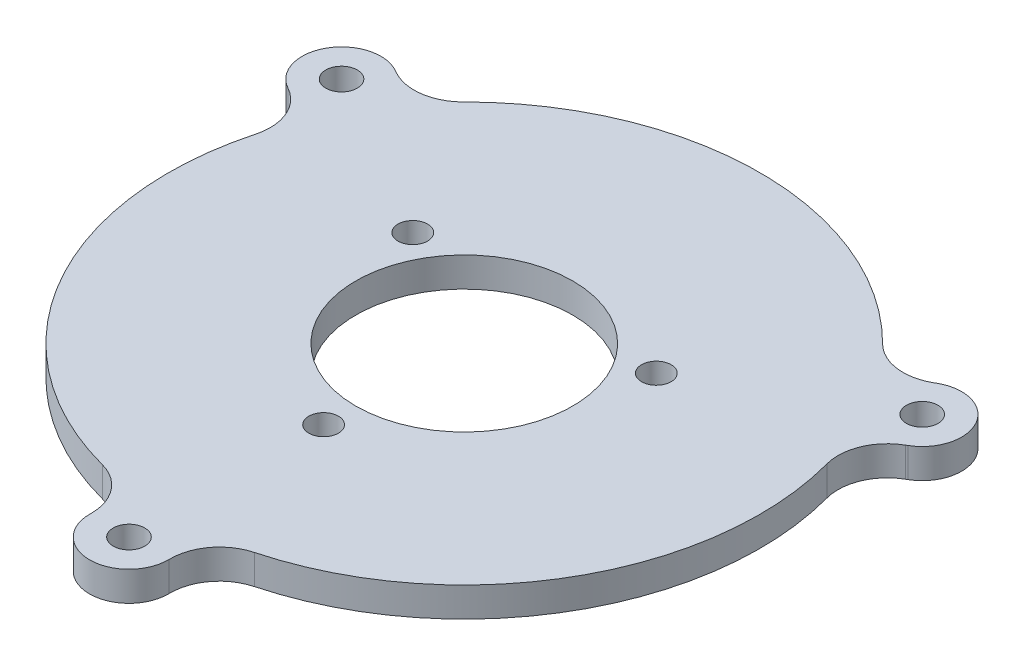
SolidWorks part; units mm, degrees
ref_plane "Front Plane" through (0, 0, 0) normal (0, 0, 1) x (1, 0, 0)
ref_plane "Top Plane" through (0, 0, 0) normal (0, 1, 0) x (1, 0, 0)
ref_plane "Right Plane" through (0, 0, 0) normal (1, 0, 0) x (0, 0, -1)
sketch "Sketch1" plane through (0, 0, 0) normal (0, 1, 0) x (1, 0, 0)
  line L1 (0, -34) -> (0, 0) construction
  circle A0 centre (-29.4449, 17) radius 1.6
  circle A1 centre (29.4449, 17) radius 1.6
  circle A2 centre (0, -34) radius 1.6
  circle A3 centre (0, 0) radius 11
  line B0 (31.2916, 13.4474) -> (31.4449, 13.5359)
  line B1 (27.4449, 20.4641) -> (27.2916, 20.3756)
  line B2 (-27.2916, 20.3756) -> (-27.4449, 20.4641)
  arc B3 (-27.4449, 20.4641) -> (-31.3766, 13.4973) centre (-29.4449, 17) ccw
  arc B4 (-28.9639, 7.8163) -> (-31.3766, 13.4973) centre (-33.7912, 9.119) ccw
  arc B5 (-28.9639, 7.8163) -> (-7.7128, -28.9916) centre (0, 0) ccw
  arc B6 (-3.9992, -33.9216) -> (-7.7128, -28.9916) centre (-8.9983, -33.8235) ccw
  arc B7 (-3.9992, -33.9216) -> (3.9992, -33.9216) centre (0, -34) ccw
  arc B8 (7.7128, -28.9916) -> (3.9992, -33.9216) centre (8.9983, -33.8235) ccw
  arc B9 (7.7128, -28.9916) -> (28.9643, 7.8148) centre (0, 0) ccw
  arc B10 (31.2916, 13.4474) -> (28.9643, 7.8148) centre (33.7916, 9.1173) ccw
  arc B11 (31.4449, 13.5359) -> (27.4449, 20.4641) centre (29.4449, 17) ccw
  arc B12 (21.25, 21.1764) -> (27.2916, 20.3756) centre (24.7916, 24.7058) ccw
  arc B13 (21.25, 21.1764) -> (-21.25, 21.1764) centre (0, 0) ccw
  arc B14 (-27.2916, 20.3756) -> (-21.25, 21.1764) centre (-24.7916, 24.7058) ccw
  circle B15 centre (-12.35, 7.1303) radius 1.5
  circle B16 centre (12.35, 7.1303) radius 1.5
  circle B17 centre (0, -14.2606) radius 1.5
  dimension "D1" = 3.2
  dimension "D2" = 22
sketch_block_instance "body_block-1"
sketch_block "body_block"
sketch_block_instance "encoder_block-1"
sketch_block "encoder_block" parameters "D1"=37.75
extrude "Boss-Extrude1" add sketch "Sketch1" along normal blind 3
